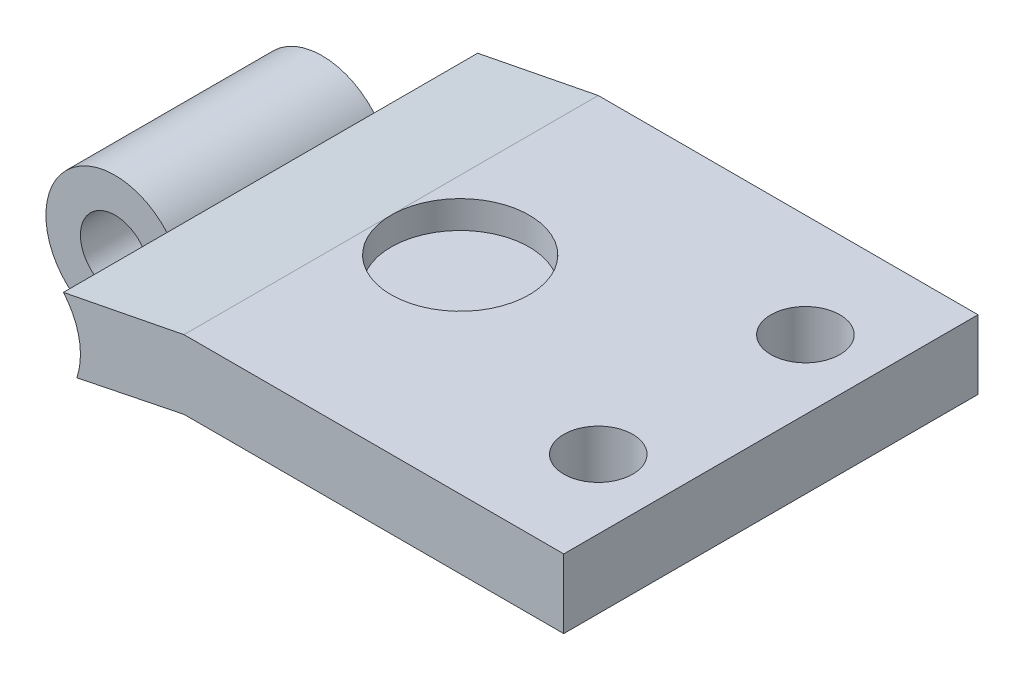
SolidWorks part; units mm, degrees
ref_plane "Ön Düzlem" through (0, 0, 0) normal (0, 0, 1) x (1, 0, 0)
ref_plane "Üst Düzlem" through (0, 0, 0) normal (0, 1, 0) x (1, 0, 0)
ref_plane "Sağ Düzlem" through (0, 0, 0) normal (1, 0, 0) x (0, 0, -1)
sketch "Çizim1" plane through (0, 0, 0) normal (0, 0, 1) x (1, 0, 0)
  line L0 (-25.0506, 3.3431) -> (-16.3184, 5.0562)
  line L1 (-24.0757, -1.5272) -> (-16.3184, 0.0562)
  line L2 (-29.2997, 2.5095) -> (-28.3371, -2.397) construction
  line L3 (-28.3371, -2.397) -> (-28.2998, -2.3894)
  line L4 (-16.3184, 0.0562) -> (3.9228, 0.0562)
  line L6 (3.9228, 5.0562) -> (-16.3184, 5.0562)
  line L7 (3.9228, 0.0562) -> (6.1828, 0.0562)
  line L9 (6.1828, 5.0562) -> (3.9228, 5.0562)
  line L10 (6.1828, 0.0562) -> (11.1828, 0.0562)
  line L11 (11.1828, 0.0562) -> (11.1828, 5.0562)
  line L12 (11.1828, 5.0562) -> (6.1828, 5.0562)
  arc A1 (-28.3371, -2.397) -> (-28.2998, -2.3894) centre (-28.8184, 0.0562) ccw
  arc A2 (-25.0506, 3.3431) -> (-24.0757, -1.5272) centre (-28.8184, 0.0562) ccw
  dimension "D1" = 2.26
  dimension "D2" = 5
extrude "Yükseklik-Ekstrüzyon1" add sketch "Çizim1" along normal blind 30
sketch "Çizim2" plane through (0, 0, 30) normal (0, 0, 1) x (1, 0, 0)
  line L0 (-28.8184, 5.0562) -> (-28.8184, -4.9438) construction
  arc A0 (-25.0506, 3.3431) -> (-24.0757, -1.5272) centre (-28.8184, 0.0562) ccw construction
  circle A1 centre (-28.8184, 0.0562) radius 2.5
  dimension "D1" = 5
extrude "Kes-Ekstrüzyon1" cut sketch "Çizim2" against normal blind 30
sketch "Çizim6" plane through (0, 0, 30) normal (0, 0, 1) x (1, 0, 0)
  circle A0 centre (-28.8184, 0.0562) radius 5
extrude "Kes-Ekstrüzyon3" cut sketch "Çizim6" against normal blind 7.5
sketch "Çizim7" plane through (0, 0, 0) normal (0, 0, -1) x (-1, 0, 0)
  circle A0 centre (28.8184, 0.0562) radius 5
extrude "Kes-Ekstrüzyon4" cut sketch "Çizim7" against normal blind 7.5
sketch "Çizim9" plane through (0, 5.0562, 0) normal (0, 1, 0) x (1, 0, 0)
  line L0 (-25.0506, -15) -> (14.5137, -15) construction
  line L1 (-25.0506, -22.5) -> (-25.0506, -7.5) construction
  line L3 (11.1828, -30) -> (11.1828, 0) construction
  circle A0 centre (-11.3172, -15) radius 5
  dimension "D1" = 10
  dimension "D2" = 22.5
extrude "Kes-Ekstrüzyon6" cut sketch "Çizim9" against normal blind 2
sketch "Çizim10" plane through (0, 5.0562, 0) normal (0, 1, 0) x (1, 0, 0)
  line L0 (6.1828, -28.6811) -> (6.1828, 6.4681) construction
  line L1 (11.1828, -30) -> (-16.3184, -30) construction
  line L2 (11.1828, 0) -> (-16.3184, 0) construction
  line L3 (11.1828, -30) -> (11.1828, 0) construction
  circle A0 centre (6.1828, -22.5) radius 2.5
  circle A1 centre (6.1828, -7.5) radius 2.5
  dimension "D1" = 5
  dimension "D2" = 5
  dimension "D3" = 7.5
  dimension "D4" = 7.5
  dimension "D5" = 5
extrude "Kes-Ekstrüzyon7" cut sketch "Çizim10" against normal blind 5
